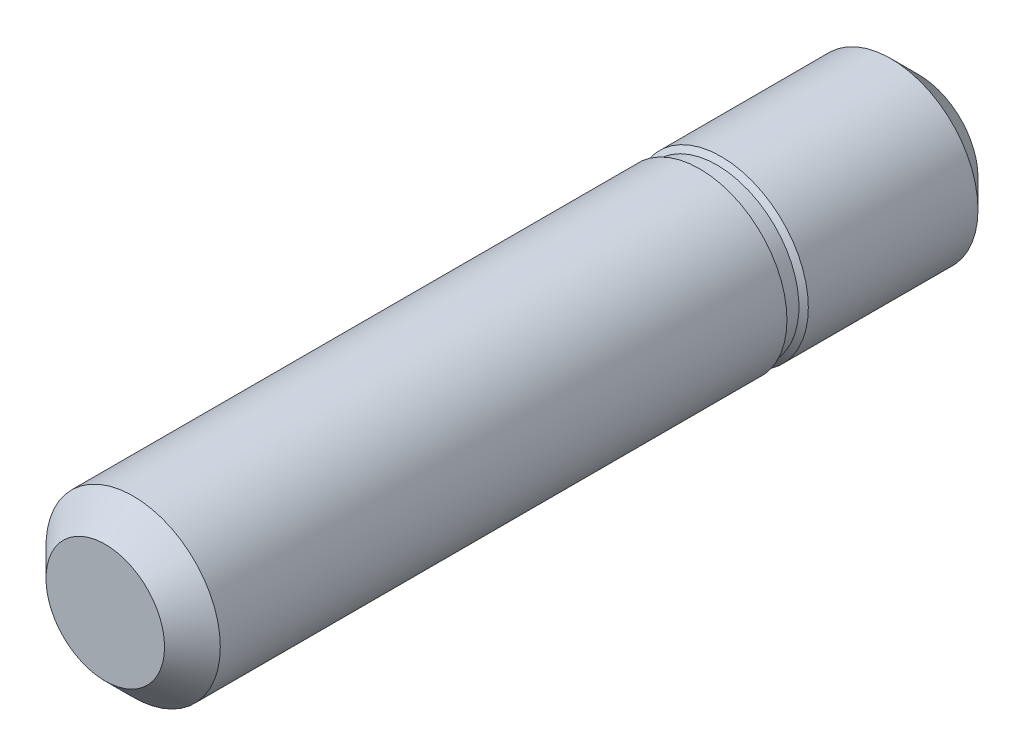
SolidWorks part; units mm, degrees
ref_plane "Front Plane" through (0, 0, 0) normal (0, 0, 1) x (1, 0, 0)
ref_plane "Top Plane" through (0, 0, 0) normal (0, 1, 0) x (1, 0, 0)
ref_plane "Right Plane" through (0, 0, 0) normal (1, 0, 0) x (0, 0, -1)
sketch "Sketch1" plane through (0, 0, 0) normal (0, 0, 1) x (1, 0, 0)
  circle A0 centre (0, 0) radius 4.7625
  dimension "D1" = 9.525
extrude "Boss-Extrude1" add sketch "Sketch1" against normal blind 44.45
sketch "Sketch2" plane through (0, 0, 0) normal (0, 1, 0) x (1, 0, 0)
  line L0 (-4.7625, 44.45) -> (-4.7625, 0) construction
  line L2 (-4.7625, 33.655) -> (-4.7625, 32.4866)
  line L3 (-4.7625, 32.4866) -> (-4.4831, 32.4866)
  line L4 (-4.4831, 33.4206) -> (-4.4831, 32.4866)
  line L5 (0, 44.45) -> (0, 39.6514) construction
  line L6 (4.7625, 44.45) -> (-4.7625, 44.45) construction
  line L7 (-4.4831, 33.4206) -> (-4.7625, 33.655)
  dimension "D1" = 1.1684
  dimension "D2" = 8.9662
  dimension "D3" = 10.795
  dimension "D4" = 40
revolve "Cut-Revolve1" cut sketch "Sketch2" angle 360 about L5
chamfer "Chamfer1" distance 1.524 distance2 1.524 2 edges at (4.7625, 0, 0) (4.7625, 0, -44.45)
